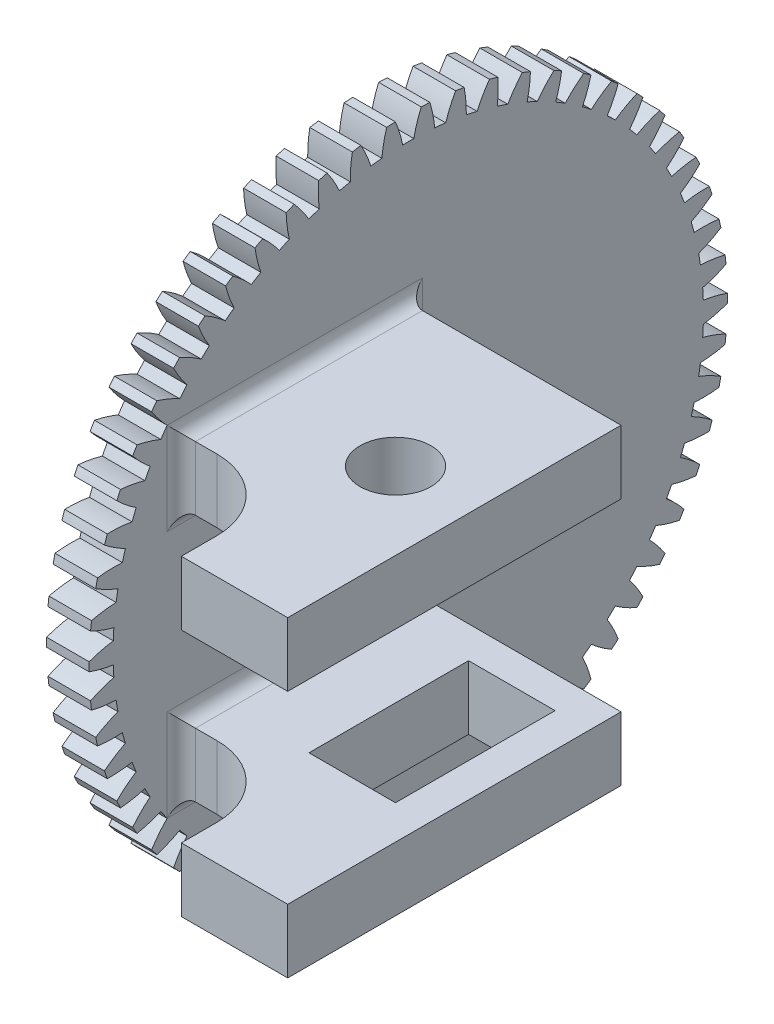
SolidWorks part; units mm, degrees
ref_plane "Plane1" through (0, 0, 0) normal (0, 0, 1) x (1, 0, 0)
ref_plane "Plane2" through (0, 0, 0) normal (0, 1, 0) x (1, 0, 0)
ref_plane "Plane3" through (0, 0, 0) normal (1, 0, 0) x (0, 0, -1)
other "Configuration Table"
sketch "HoldingSke" plane through (0, 0, 0) normal (0, 1, 0) x (1, 0, 0)
  line L0 (0, 0) -> (0.3533, -0.5654)
  line L1 (-15, 0) -> (100, 0) construction
  line L2 (0, 0) -> (-2.1039, 2.3779)
  line L3 (0, 0) -> (-11.863, 4.5341)
  line L4 (0, 0) -> (4.5764, 7.3237)
  line L5 (0, 0) -> (-46.8476, -17.4728)
  line L6 (0, 0) -> (-4.9738, -3.3558)
  line L7 (-2.1039, 2.3779) -> (8.6586, 51.2059)
  line L8 (-76.2, 54.61) -> (-74.8, 54.61)
  line L9 (-67.7845, 28.3722) -> (-49.3413, 33.142)
  line L10 (-76.2, 71.12) -> (104.1128, 71.12)
  line L11 (0, 0) -> (-6, 0)
  line L12 (-76.2, 101.6) -> (-76.147, 101.6)
  line L13 (24.9733, 27.94) -> (52.9518, 28.4284)
  line L14 (24.9733, 27.94) -> (24.9743, 27.94)
  line L15 (24.9733, 27.94) -> (100.4006, 29.5858)
  line L16 (-63.627, -1.5) -> (-12.827, -1.5)
  circle A0 centre (0, 0) radius 4
  circle A1 centre (0, 0) radius 37.5
  circle A2 centre (0, 0) radius 37.5
  circle A3 centre (0, 0) radius 4
  dimension "MHD" = 75
  dimension "Hub_dia" = 75
  dimension "Bore" = 8
  dimension "MBD" = 8
  dimension "Num_teeth" = 58
  dimension "Pitch" = 0.6667
  dimension "Overall_len" = 50
  dimension "Show_teeth" = 58
  dimension "Thickness" = 6
  dimension "OAL" = 50.0001
  dimension "T_dim" = 1.4
  dimension "Ap" = 14.5
  dimension "H" = 19.05
  dimension "Pitch_radius" = 180.3128
  dimension "Width" = 6
  dimension "Backlash" = 0.053
  dimension "Addendum_fac" = 1
  dimension "Dedendum_fac" = 1.25
  dimension "Clearance_fac" = 0.25
  dimension "Dedendum_add" = 0.001
  dimension "Module" = 1.5
sketch "BasProSke" plane through (0, 0, 0) normal (0, 1, 0) x (1, 0, 0)
  line L0 (-10, 0) -> (60, 0) construction
  line L1 (0, 0) -> (0, 45)
  line L2 (0, 0) -> (6, 0)
  line L3 (6, 0) -> (6, 45)
  line L4 (6, 45) -> (0, 45)
  dimension "Thickness" = 6
  dimension "Diameter" = 90
revolve "Base-Revolve" add sketch "BasProSke" angle 360 about L0
sketch "TooCutSke" plane through (0, 0, 0) normal (1, 0, 0) x (0, 0, -1)
  line L1 (0, 0) -> (0, 107) construction
  line L2 (0, 0) -> (-1.2707, 43.4814) construction
  line L3 (0, 0) -> (-4.7086, 86.8454) construction
  line L4 (-1.2707, 43.4814) -> (-2.3543, 43.4227) construction
  arc A0 (0.7828, 41.6166) -> (-0.7828, 41.6166) centre (0, 0) ccw
  arc A1 (1.8336, 44.9881) -> (-1.8336, 44.9881) centre (0, 0) ccw
  circle A2 centre (0, 0) radius 43.5 construction
  circle A3 centre (0, 0) radius 42.1144 construction
  arc A4 (-0.7828, 41.6166) -> (-1.8336, 44.9881) centre (-17.8344, 38.1518) ccw
  arc A5 (1.8336, 44.9881) -> (0.7828, 41.6166) centre (17.8344, 38.1518) ccw
  dimension "Root_dia" = 83.248
  dimension "Overcut_dia" = 90.0508
  dimension "Pitch_dia" = 87
  dimension "Base_dia" = 84.2288
  dimension "Flank_rad" = 17.4
  dimension "Half_ang" = 3.103
  dimension "Half_CT" = 1.0852
extrude "ToothCut" cut sketch "TooCutSke" along normal through all
fillet "Breaks" [suppressed] radius 0.03
fillet "RootFillets" [suppressed] radius 0.376
pattern_circular "TeethCuts" count 58 every 6.207 about axis through (-10, 0, 0) along (1, 0, 0) of "ToothCut", "RootFillets", "Breaks"
sketch "HubNeaOneSke" plane through (0, 0, 0) normal (-1, 0, 0) x (0, 0, 1)
  circle A0 centre (0, 0) radius 37.5
  dimension "Diameter" = 75
extrude "HubNearOne" [suppressed] add sketch "HubNeaOneSke" along normal blind 44.0001
sketch "HubNeaBotSke" plane through (0, 0, 0) normal (-1, 0, 0) x (0, 0, 1)
  circle A0 centre (0, 0) radius 37.5
  dimension "Diameter" = 75
extrude "HubNearBoth" [suppressed] add sketch "HubNeaBotSke" along normal blind 22
ref_plane "FarPln" through (6, 0, 0) normal (1, 0, 0) x (0, 0, -1)
sketch "HubFarSke" plane through (6, 0, 0) normal (1, 0, 0) x (0, 0, -1)
  circle A0 centre (0, 0) radius 37.5
  dimension "Diameter" = 75
extrude "HubFar" [suppressed] add sketch "HubFarSke" along normal blind 22
sketch "BorSke" plane through (0, 0, 0) normal (1, 0, 0) x (0, 0, -1)
  circle A0 centre (0, 0) radius 4
  dimension "Diameter" = 8
extrude "Bore" cut sketch "BorSke" along normal mid plane 100.0001
sketch "KeySke" plane through (0, 0, 0) normal (1, 0, 0) x (0, 0, -1)
  line L0 (-1.5, 0) -> (-1.5, 5.4)
  line L1 (-1.5, 5.4) -> (1.5, 5.4)
  line L2 (1.5, 5.4) -> (1.5, 0)
  line L3 (0, 0) -> (0, 34) construction
  line L4 (-1.5, 0) -> (1.5, 0)
  dimension "Offset" = 5.4
  dimension "Width" = 3
extrude "Keyway" [suppressed] cut sketch "KeySke" along normal mid plane 100.0001
pattern_circular "Keyway2" [suppressed] count 2 every 90 about axis through (-10, 0, 0) along (1, 0, 0)
sketch "Esquisse1" plane through (6, 0, 0) normal (1, 0, 0) x (0, 0, -1)
  circle A0 centre (0, 0) radius 10
extrude "Enlèv. mat.-Extru.1" cut sketch "Esquisse1" against normal through all
sketch "Esquisse2" plane through (6, 0, 0) normal (1, 0, 0) x (0, 0, -1)
  line L1 (0, 0) -> (35, 0)
  line L2 (0, 0) -> (0, 22)
  line L3 (0, 22) -> (35, 22)
  line L4 (35, 0) -> (35, 22)
  line L5 (0, 0) -> (35, 0)
  line L6 (0, 0) -> (0, -22)
  line L7 (0, -22) -> (35, -22)
  line L8 (35, 0) -> (35, -22)
  line L9 (0, 0) -> (-32, 0)
  line L10 (0, 0) -> (0, -22)
  line L11 (0, -22) -> (-32, -22)
  line L12 (-32, 0) -> (-32, -22)
  line L13 (0, 0) -> (-32, 0)
  line L14 (0, 0) -> (0, 22)
  line L15 (0, 22) -> (-32, 22)
  line L16 (-32, 0) -> (-32, 22)
  line L17 (-32, 22) -> (6, 22)
  line L18 (-32, 22) -> (-32, 13)
  line L19 (-32, 13) -> (6, 13)
  line L20 (6, 22) -> (6, 13)
  line L21 (-32, -22) -> (6, -22)
  line L22 (-32, -22) -> (-32, -13)
  line L23 (-32, -13) -> (6, -13)
  line L24 (6, -22) -> (6, -13)
  dimension "D1" = 32
  dimension "D2" = 32
  dimension "D3" = 35
  dimension "D4" = 35
  dimension "D5" = 22
  dimension "D6" = 22
  dimension "D7" = 22
  dimension "D8" = 22
  dimension "D9" = 13
  dimension "D10" = 13
  dimension "D11" = 38
  dimension "D12" = 38
extrude "Boss.-Extru.1" add sketch "Esquisse2" along normal blind 30 contours L20 L15 L16 L19 | L11 L24 L23 L12
sketch "Esquisse6" plane through (0, -22, 0) normal (0, -1, 0) x (1, 0, 0)
  line L0 (6, 0) -> (6, 32) construction
  line L1 (19, 27) -> (31.2, 27)
  line L2 (19, 27) -> (19, 4.5)
  line L3 (19, 4.5) -> (31.2, 4.5)
  line L4 (31.2, 27) -> (31.2, 4.5)
  line L6 (36, 0) -> (6, 0) construction
  dimension "D1" = 12.2
  dimension "D2" = 22.5
  dimension "D3" = 13
  dimension "D4" = 4.5
extrude "Enlèv. mat.-Extru.4" cut sketch "Esquisse6" against normal blind 10
fillet "Congé1" radius 2 8 edges at (6, -22, 16) (6, 17.5, 0) (6, 22, 16) (6, 17.5, 32) (6, 13, 16) (6, -17.5, 0) (6, -13, 16) (6, -17.5, 32)
sketch "Esquisse8" plane through (0, 22, 0) normal (0, 1, 0) x (1, 0, 0)
  line L0 (36, 0) -> (36, -32) construction
  line L1 (36, -32) -> (8, -32) construction
  circle A0 centre (25.1, -20.9) radius 5
  dimension "D1" = 10
  dimension "D2" = 10.9
  dimension "D3" = 11.1
extrude "Enlèv. mat.-Extru.5" cut sketch "Esquisse8" against normal blind 17
sketch "Esquisse9" plane through (0, 0, 32) normal (0, 0, 1) x (1, 0, 0)
  line L0 (36, 13) -> (8, 13) construction
  line L1 (36, 22) -> (21, 22)
  line L2 (36, 22) -> (36, 13)
  line L3 (36, 13) -> (21, 13)
  line L4 (21, 22) -> (21, 13)
  line L5 (-19.404, 0) -> (55.844, 0) construction
  line L6 (36, -22) -> (36, -13)
  line L7 (36, -13) -> (21, -13)
  line L8 (36, -22) -> (21, -22)
  line L9 (21, -22) -> (21, -13)
  dimension "D1" = 15
extrude "Boss.-Extru.2" add sketch "Esquisse9" along normal blind 15
fillet "Congé2" radius 10 2 edges at (21, -17.5, 32) (21, 17.5, 32)
equation "' \"Module@HoldingSke\" = 6.35"
equation "' \"Num_teeth@HoldingSke\" = 12"
equation "' \"Ap@HoldingSke\" =  20"
equation "' \"Ap@HoldingSke\" = 20"
equation "' \"Width@HoldingSke\" = 0.5 * 25.4"
equation "' \"Hub_dia@HoldingSke\"= 1 * 25.4"
equation "' \"Hub_dia@HoldingSke\" = 1 * 25.4"
equation "' \"Overall_len@HoldingSke\" = 1.0 * 25.4"
equation "' \"Bore@HoldingSke\" = 0.75 * 25.4"
equation "' \"T_dim@HoldingSke\" = 0.1 * 25.4"
equation "' \"Width@KeySke\" = 0.25 * 25.4"
equation "' \"Show_teeth@HoldingSke\" = 13"
equation "' \"Backlash@HoldingSke\" = 0.009 * 25.4"
equation "' \"Addendum_fac@HoldingSke\" = 1.0"
equation "' \"Dedendum_fac@HoldingSke\" = 1.25"
equation "' \"Dedendum_add@HoldingSke\" = 0.00005 * 25.4"
equation "' \"Clearance_fac@HoldingSke\" = 0.25"
equation "\"Pitch@HoldingSke\" = 1 / \"Module@HoldingSke\""
equation "\"Overcut_dia@TooCutSke\" = (\"Num_teeth@HoldingSke\" + 2 * \"Addendum_fac@HoldingSke\") / \"Pitch@HoldingSke\" + 0.002 * 25.4"
equation "\"Pitch_dia@TooCutSke\" = \"Num_teeth@HoldingSke\" / \"Pitch@HoldingSke\""
equation "\"Base_dia@TooCutSke\" = \"Num_teeth@HoldingSke\" / \"Pitch@HoldingSke\" * cos((\"Ap@HoldingSke\"  * 3.14159265 / 180))"
equation "\"Root_dia@TooCutSke\" = (\"Num_teeth@HoldingSke\" + 2) / \"Pitch@HoldingSke\" - 2 * (\"Addendum_fac@HoldingSke\" + \"Dedendum_fac@HoldingSke\") / \"Pitch@HoldingSke\" - \"Dedendum_add@HoldingSke\" * 2"
equation "\"Half_ang@TooCutSke\" = 180 / \"Num_teeth@HoldingSke\""
equation "\"Half_CT@TooCutSke\" = \"Num_teeth@HoldingSke\" / \"Pitch@HoldingSke\" * sin((3.14159265 / 2 / \"Num_teeth@HoldingSke\")) / 2 - 7 * \"Backlash@HoldingSke\" / 4"
equation "\"Flank_rad@TooCutSke\" = \"Num_teeth@HoldingSke\" / \"Pitch@HoldingSke\" / 5"
equation "\"Radius@RootFillets\" = \"Clearance_fac@HoldingSke\" / \"Pitch@HoldingSke\" + \"Dedendum_add@HoldingSke\""
equation "\"Break_rad@Breaks\" = 0.02 / \"Pitch@HoldingSke\""
equation "\"Thickness@HoldingSke\" = \"Width@HoldingSke\""
equation "\"OAL@HoldingSke\" = \"Thickness@HoldingSke\""
equation "\"MHD@HoldingSke\" = (\"Num_teeth@HoldingSke\" + 2) / \"Pitch@HoldingSke\" - 2 * (\"Addendum_fac@HoldingSke\" + \"Dedendum_fac@HoldingSke\")  / \"Pitch@HoldingSke\" - \"Dedendum_add@HoldingSke\" * 2"
equation "\"MBD@HoldingSke\" = (\"Num_teeth@HoldingSke\" + 2) / \"Pitch@HoldingSke\" - 2 * (\"Addendum_fac@HoldingSke\" + \"Dedendum_fac@HoldingSke\")  / \"Pitch@HoldingSke\" - \"Dedendum_add@HoldingSke\" * 2 - 0.002 * 25.4"
equation "\"MHD@HoldingSke\" = ((sgn( \"MHD@HoldingSke\" - \"Hub_dia@HoldingSke\" )-1)*( \"MHD@HoldingSke\" - \"Hub_dia@HoldingSke\" ))/-2+ \"Hub_dia@HoldingSke\""
equation "\"MBD@HoldingSke\" = ((sgn( \"MBD@HoldingSke\" - \"Bore@HoldingSke\" )-1)*( \"MBD@HoldingSke\" - \"Bore@HoldingSke\" ))/-2+ \"Bore@HoldingSke\""
equation "\"OAL@HoldingSke\" = ((sgn( \"OAL@HoldingSke\" - \"Overall_len@HoldingSke\" )+1)*( \"OAL@HoldingSke\" - \"Overall_len@HoldingSke\" ))/2 + \"Overall_len@HoldingSke\" + 0.000002 * 25.4"
equation "\"Num_teeth@TeethCuts\" = int( \"Show_teeth@HoldingSke\" ) + 1"
equation "\"Num_teeth@TeethCuts\" = ((sgn( \"Num_teeth@TeethCuts\" - \"Num_teeth@HoldingSke\" )-1)*( \"Num_teeth@TeethCuts\" - \"Num_teeth@HoldingSke\" ))/-2+ \"Num_teeth@HoldingSke\""
equation "\"Num_teeth@TeethCuts\" = ((sgn( \"Num_teeth@TeethCuts\" - 2.0)+1)*( \"Num_teeth@TeethCuts\" - 2.0))/2 +2.0"
equation "\"Angle@TeethCuts\" = 360.0 / \"Num_teeth@HoldingSke\""
equation "\"Diameter@BasProSke\" = (\"Num_teeth@HoldingSke\" + 2 * \"Addendum_fac@HoldingSke\") / \"Pitch@HoldingSke\""
equation "\"Thickness@BasProSke\"  = \"Thickness@HoldingSke\""
equation "' \"Fillet_rad@BasProSke\" =  \"Thickness@HoldingSke\" * 0.05"
equation "' \"Fillet_rad@BasProSke\" = \"Thickness@HoldingSke\" * 0.05"
equation "\"MHD@HoldingSke\" = ((sgn( \"MHD@HoldingSke\" - \"Root_dia@TooCutSke\" )-1)*( \"MHD@HoldingSke\" - \"Root_dia@TooCutSke\" ))/-2+ \"Root_dia@TooCutSke\""
equation "\"Diameter@HubNeaOneSke\" = \"MHD@HoldingSke\""
equation "\"Length@HubNearOne\" = \"OAL@HoldingSke\" - \"Thickness@BasProSke\""
equation "\"Diameter@HubNeaBotSke\" = \"MHD@HoldingSke\""
equation "\"Length@HubNearBoth\" = ( \"OAL@HoldingSke\" - \"Thickness@BasProSke\" ) / 2.0"
equation "\"Thickness@FarPln\" = \"Thickness@BasProSke\""
equation "\"Diameter@HubFarSke\" = \"MHD@HoldingSke\""
equation "\"Length@HubFar\" = ( \"OAL@HoldingSke\" - \"Thickness@BasProSke\" ) / 2.0"
equation "\"Diameter@BorSke\" = \"MBD@HoldingSke\""
equation "\"D1@Bore\" = \"OAL@HoldingSke\" * 2.0"
equation "\"D1@Keyway\" = \"OAL@HoldingSke\" * 2.0"
equation "\"Offset@KeySke\" = \"T_dim@HoldingSke\" + \"MBD@HoldingSke\" / 2.0"
